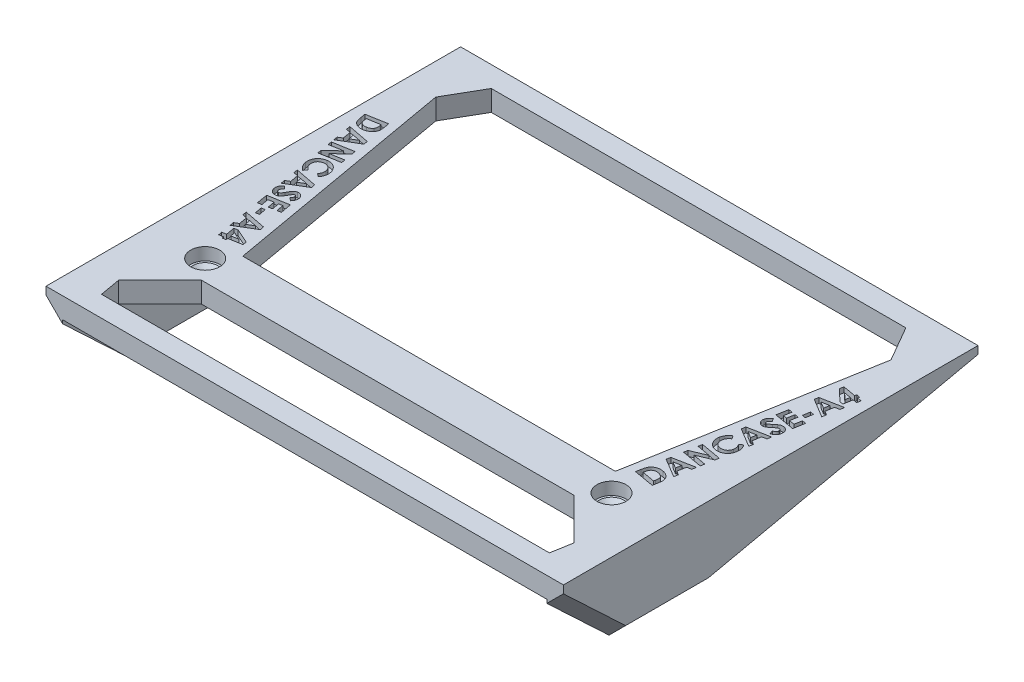
SolidWorks part; units mm, degrees
ref_plane "Front Plane" through (0, 0, 0) normal (0, 0, 1) x (1, 0, 0)
ref_plane "Top Plane" through (0, 0, 0) normal (0, 1, 0) x (1, 0, 0)
ref_plane "Right Plane" through (0, 0, 0) normal (1, 0, 0) x (0, 0, -1)
sketch "Sketch1" plane through (0, 0, 0) normal (0, 0, 1) x (1, 0, 0)
  line L0 (-58.4, 0) -> (58.4, 0)
  line L1 (-58.4, 0) -> (-58.4, -15)
  line L2 (-58.4, -15) -> (-62.4, -11)
  line L3 (-62.4, -11) -> (-62.4, 5)
  line L4 (-62.4, 5) -> (62.4, 5)
  line L5 (0, 0) -> (0, 50000) construction
  line L6 (58.4, 0) -> (58.4, -15)
  line L7 (58.4, -15) -> (62.4, -11)
  line L8 (62.4, -11) -> (62.4, 5)
  point P4 (0, 0)
  point P14 (0, 5)
  dimension "D1" = 116.8
  dimension "D2" = 5
  dimension "D3" = 4
  dimension "D4" = 45
  dimension "D5" = 15
extrude "Boss-Extrude1" add sketch "Sketch1" along normal mid plane 20
sketch "Sketch2" plane through (0, 5, 0) normal (0, 1, 0) x (1, 0, 0)
  line L0 (49, 0) -> (-49, 0) construction
  line L1 (0, 10) -> (0, -10) construction
  line L2 (62.4, -10) -> (-62.4, -10) construction
  circle A0 centre (49, 0) radius 3.5
  circle A1 centre (-49, 0) radius 3.5
  point P4 (0, 0)
  point P11 (0, 0)
  dimension "D2" = 7
  dimension "D1" = 98
extrude "Cut-Extrude1" cut sketch "Sketch2" against normal offset from surface (3 mm away) 2 up to face at (0, 0, 0)
sketch "Sketch3" plane through (0, 2, 0) normal (0, 1, 0) x (1, 0, 0)
  line L0 (0, 10) -> (0, -10) construction
  line L1 (62.4, -10) -> (-62.4, -10) construction
  circle A0 centre (49, 0) radius 3.5 construction
  circle A1 centre (49, 0) radius 3.5 construction
  circle A2 centre (49, 0) radius 1.5
  circle A3 centre (-49, 0) radius 1.5
  point P10 (0, 0)
  dimension "D1" = 3
extrude "Cut-Extrude2" cut sketch "Sketch3" against normal through all
chamfer "Chamfer1" distance 1.5 angle 45 2 edges at (47.5, 2, 0) (-47.5, 2, 0)
ref_plane "Plane1" through (0, 0, -75) normal (0, 0, 1) x (1, 0, 0)
sketch "Sketch4" plane through (0, 0, -75) normal (0, 0, 1) x (1, 0, 0)
  line L0 (58.4, -0.8579) -> (62.4, 3.1421)
  line L1 (-58.4, -0.8579) -> (-62.4, 3.1421)
  line L2 (51.3289, -7.9289) -> (55.3289, -3.9289) construction
  line L3 (62.4, -11) -> (62.4, 5) construction
  line L4 (58.4, 0) -> (58.4, -15) construction
  line L5 (-55.3289, -3.9289) -> (-51.3289, -7.9289) construction
  line L6 (-62.4, 5) -> (-62.4, -11) construction
  line L7 (-58.4, -15) -> (-58.4, 0) construction
  line L8 (58.4, 0) -> (58.4, -15)
  line L9 (-58.4, 0) -> (58.4, 0)
  line L10 (-58.4, -15) -> (-58.4, 0)
  line L11 (-62.4, -11) -> (-58.4, -15)
  line L12 (-62.4, 5) -> (-62.4, -11)
  line L13 (62.4, 5) -> (-62.4, 5)
  line L14 (62.4, -11) -> (62.4, 5)
  line L15 (58.4, -15) -> (62.4, -11)
  line L16 (58.4, 0) -> (58.4, -0.8579)
  line L17 (-58.4, 0) -> (58.4, 0)
  line L18 (-58.4, -0.8579) -> (-58.4, 0)
  line L19 (-62.4, -11) -> (-58.4, -15) construction
  line L20 (-62.4, 5) -> (-62.4, 3.1421)
  line L21 (62.4, 5) -> (-62.4, 5)
  line L22 (62.4, 3.1421) -> (62.4, 5)
  line L23 (58.4, -15) -> (62.4, -11) construction
  point P10 (0, 0)
  point P12 (63.4, 3.9756)
  point P18 (58.4, -1.0825)
  point P21 (0, 0)
  point P22 (-63.4, 4.1421)
  point P27 (-58.4, -0.8579)
  point P30 (0, 0)
  dimension "D1" = 0
  dimension "D2" = 10
loft "Loft1" add profiles "Sketch4" section "Sketch4" section face at (0, -5.25, -10)
ref_plane "Plane2" through (0, 0, 25) normal (0, 0, 1) x (1, 0, 0)
sketch "Sketch5" plane through (0, 0, 25) normal (0, 0, 1) x (1, 0, 0)
  line L14 (-58.4, 0) -> (58.4, 0)
  line L15 (-58.4, -0.8579) -> (-58.4, 0)
  line L24 (-62.4, 3.1421) -> (-58.4, -0.8579)
  line L25 (-62.4, 5) -> (-62.4, 3.1421)
  line L26 (62.4, 5) -> (-62.4, 5)
  line L27 (62.4, 3.1421) -> (62.4, 5)
  line L28 (58.4, -0.8579) -> (62.4, 3.1421)
  line L29 (58.4, 0) -> (58.4, -0.8579)
  line L30 (-58.4, 0) -> (58.4, 0)
  line L31 (-58.4, -0.8579) -> (-58.4, 0)
  line L32 (-62.4, 3.1421) -> (-58.4, -0.8579)
  line L33 (-62.4, 5) -> (-62.4, 3.1421)
  line L34 (62.4, 5) -> (-62.4, 5)
  line L35 (62.4, 3.1421) -> (62.4, 5)
  line L36 (58.4, -0.8579) -> (62.4, 3.1421)
  line L37 (58.4, 0) -> (58.4, -0.8579)
  point P10 (0, 0)
  point P12 (63.4, 3.9756)
  point P18 (58.4, -1.0825)
  point P21 (0, 0)
  point P22 (-63.4, 4.1421)
  point P27 (-58.4, -0.8579)
  point P30 (0, 0)
  dimension "D1" = 0
loft "Loft2" add profiles "Sketch5" section face at (0, -5.25, 10) section "Sketch5"
sketch "Sketch6" plane through (0, 5, 0) normal (0, 1, 0) x (1, 0, 0)
  line L0 (44.9352, 5) -> (-44.9352, 5)
  line L19 (-44.9352, 5) -> (-54.9, 61.513)
  line L20 (-54.9, 61.513) -> (-50, 70)
  line L21 (-50, 70) -> (50, 70)
  line L22 (50, 70) -> (54.9, 61.513)
  line L23 (54.9, 61.513) -> (44.9352, 5)
  line L24 (0, -25) -> (0, 75) construction
  line L25 (-11.0001, -25) -> (11.0001, -25) construction
  line L26 (-11.0001, 75) -> (11.0001, 75) construction
  line L27 (62.4, -25) -> (62.4, 75) construction
  line L28 (44.9352, -5) -> (-44.9352, -5)
  line L29 (-44.9352, -5) -> (-54.9, -14.9648)
  line L30 (-54.9, -14.9648) -> (-54.0122, -20)
  line L31 (-54.0122, -20) -> (54.0122, -20)
  line L32 (54.0122, -20) -> (54.9, -14.9648)
  line L33 (54.9, -14.9648) -> (44.9352, -5)
  point P9 (53.2047, -15.5365)
  point P21 (0, 0)
  point P22 (-54.1512, -20)
  point P23 (0, 0)
  point P24 (50, -20)
  point P25 (51.73, -5)
  point P26 (46.2406, -5)
  point P27 (55.9, -14.6517)
  point P28 (0, 0)
  point P29 (55.9, -13.6194)
  point P30 (0, 0)
  dimension "D1" = 100
  dimension "D2" = 120
  dimension "D3" = 100
  dimension "D4" = 5
  dimension "D5" = 5
  dimension "D6" = 7.5
  dimension "D7" = 5
  dimension "D8" = 5
  dimension "D9" = 135
  dimension "D10" = 100
extrude "Cut-Extrude3" cut sketch "Sketch6" against normal through all
sketch "Sketch7" plane through (0, 5, 0) normal (0, 1, 0) x (1, 0, 0)
  line L1 (0, 0) -> (0, 50000) construction
  line L2 (51.8289, 3.7845) -> (61.7937, 60.2974)
  line L3 (52.21, 5.9458) -> (61.7937, 60.2974) construction
  line L4 (-52.21, 5.9458) -> (-61.7937, 60.2974) construction
  text T0 "<b>DANCASE-A4</b>" font "Century Gothic" height 5
  text T1 "<b>DANCASE-A4</b>" font "Century Gothic" height 5
  dimension "D1" = 7
extrude "Cut-Extrude4" cut sketch "Sketch7" against normal blind 1.25
